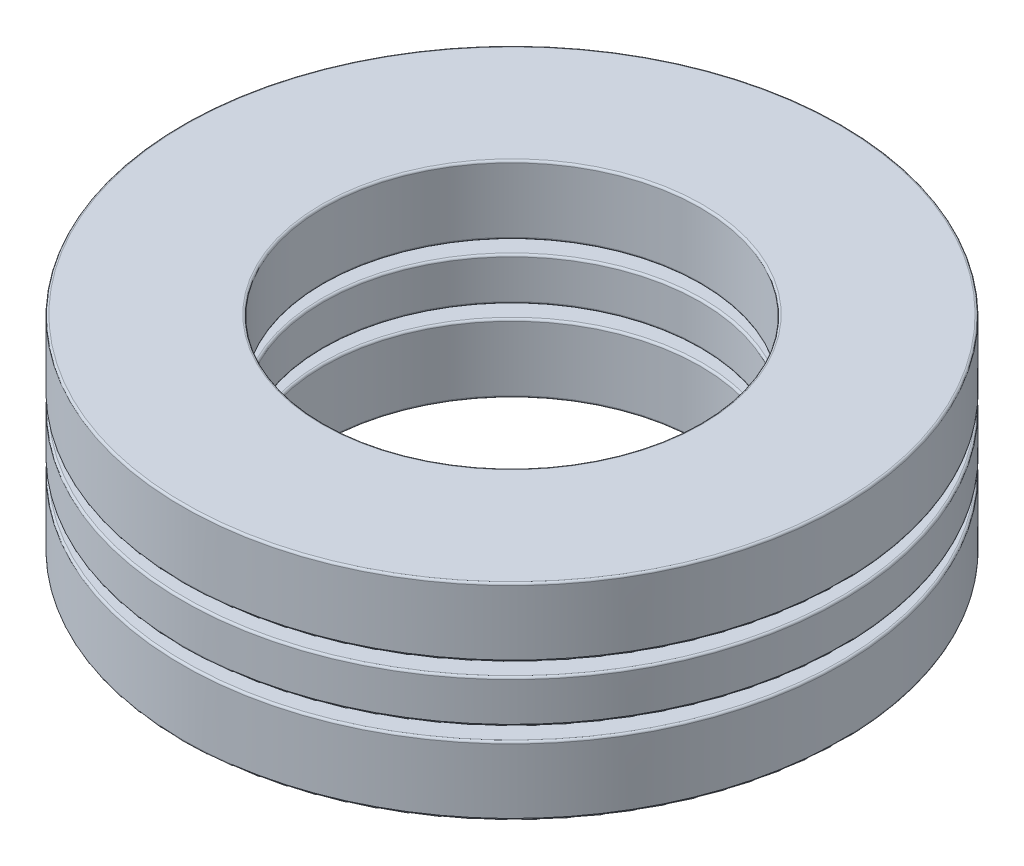
SolidWorks part; units mm, degrees
ref_plane "Front Plane" through (0, 0, 0) normal (0, 0, 1) x (1, 0, 0)
ref_plane "Top Plane" through (0, 0, 0) normal (0, 1, 0) x (1, 0, 0)
ref_plane "Right Plane" through (0, 0, 0) normal (1, 0, 0) x (0, 0, -1)
sketch "Sketch1" plane through (0, 0, 0) normal (1, 0, 0) x (0, 0, -1)
  line L0 (-14, 0) -> (14, 0) construction
  line L1 (0, -4.37) -> (0, 4.37) construction
  line L2 (-14, 0.9104) -> (-8, 0.9104)
  line L3 (-14, 0.9104) -> (-14, -0.9104)
  line L4 (-14, -0.9104) -> (-8, -0.9104)
  line L5 (-8, 0.9104) -> (-8, -0.9104)
  line L6 (-11, 1.4567) -> (-11, -1.4567) construction
  circle A0 centre (-11, 0) radius 1.4567 construction
  point P13 (-11, 0.9104)
  dimension "D1" = 2.9133
  dimension "OD" = 28
  dimension "Shaft Dia" = 16
  dimension "Th" = 8.74
  dimension "D2" = 1.8208
revolve "Revolve1" add sketch "Sketch1" angle 360 about L1
sketch "Sketch3" plane through (0, 0, 0) normal (1, 0, 0) x (0, 0, -1)
  line L0 (-11, 1.4567) -> (-11, -1.4567)
  arc A0 (-11, 1.4567) -> (-11, -1.4567) centre (-11, 0) ccw
  circle A1 centre (-11, 0) radius 1.4567 construction
revolve "Cut-Revolve1" cut sketch "Sketch3" angle 360 about L0
sketch "Sketch2" plane through (0, 0, 0) normal (1, 0, 0) x (0, 0, -1)
  line L0 (-11, 1.4567) -> (-11, -1.4567)
  arc A0 (-11, 1.4567) -> (-11, -1.4567) centre (-11, 0) ccw
  circle A2 centre (-11, 0) radius 1.4567 construction
revolve "Revolve2" add sketch "Sketch2" angle 360 about L0
ref_axis "Axis1" through (0, 4.37, 0) along (0, -1, 0)
pattern_circular "CirPattern1" count 7 every 51.429 about axis through (0, 4.37, 0) along (0, -1, 0) of bodies 187
pattern_circular "CirPattern2" count 7 every 51.429 about axis through (0, 0, 0) along (0, 1, 0) of "Cut-Revolve1"
sketch "Sketch4" plane through (0, 0, 0) normal (1, 0, 0) x (0, 0, -1)
  line L0 (-14, 0.9104) -> (-14, -0.9104) construction
  line L1 (-14, 1.4567) -> (-8, 1.4567)
  line L2 (-14, 1.4567) -> (-14, 4.37)
  line L3 (-14, 4.37) -> (-8, 4.37)
  line L4 (-8, 1.4567) -> (-8, 4.37)
  line L5 (-14, -4.37) -> (-8, -4.37)
  line L6 (-14, -4.37) -> (-14, -1.4567)
  line L7 (-14, -1.4567) -> (-8, -1.4567)
  line L8 (-8, -4.37) -> (-8, -1.4567)
  line L9 (-11, 1.4567) -> (-11, -1.4567) construction
  line L10 (-8, 0.9104) -> (-8, -0.9104) construction
  line L11 (0, 0) -> (-14, 0) construction
  line L12 (-14, 0) -> (14, 0) construction
  dimension "Ht" = 8.74
revolve "Revolve3" add sketch "Sketch4" angle 360 about L1
fillet "Fillet1" radius 0.0874 4 edges at (0, 1.4567, -8) (0, 4.37, -8) (0, 1.4567, -14) (0, 4.37, -14)
fillet "Fillet2" radius 0.0874 4 edges at (0, -0.9104, -8) (0, 0.9104, -8) (0, -0.9104, -14) (0, 0.9104, -14)
fillet "Fillet3" radius 0.0874 4 edges at (0, -4.37, -8) (0, -1.4567, -8) (0, -4.37, -14) (0, -1.4567, -14)
equation "\"D1@Sketch1\" = \"Th@Sketch1\"/3"
equation "\"D2@Sketch1\" = \"D1@Sketch1\"*.625"
equation "\"Balls@CirPattern1\" = \"OD@Sketch1\"*.25"
equation "\"Angle@CirPattern1\" = 360/\"Balls@CirPattern1\""
equation "\"D1@CirPattern2\" = \"Balls@CirPattern1\""
equation "\"D2@CirPattern2\" = \"Angle@CirPattern1\""
equation "\"D1@Fillet1\" = \"Th@Sketch1\"*.01"
equation "\"D1@Fillet2\" = \"D1@Fillet1\""
equation "\"D1@Fillet3\" = \"D1@Fillet1\""
